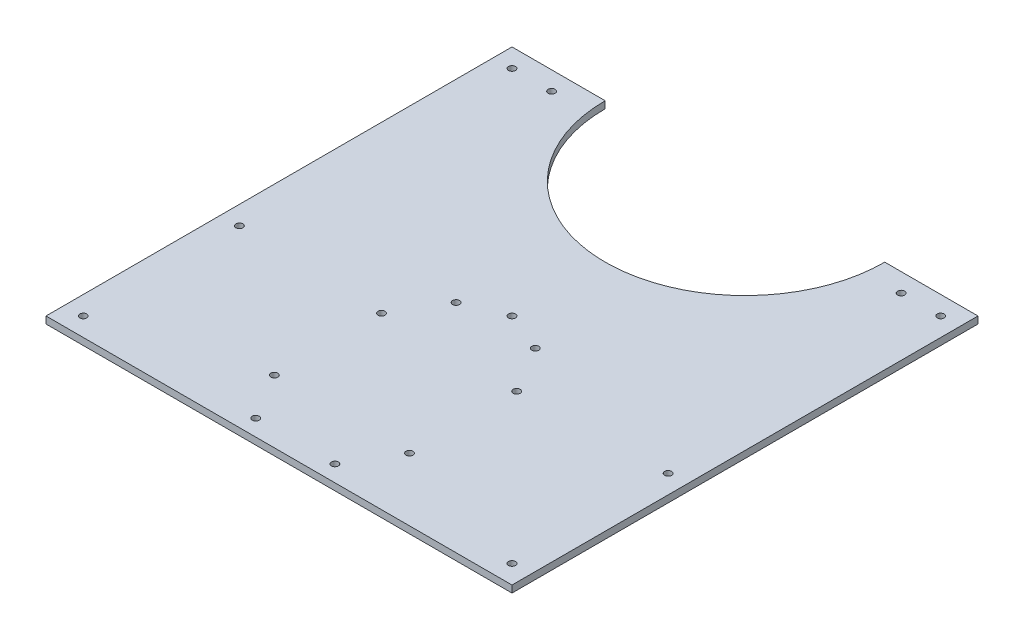
SolidWorks part; units mm, degrees
ref_plane "Front Plane" through (0, 0, 0) normal (0, 0, 1) x (1, 0, 0)
ref_plane "Top Plane" through (0, 0, 0) normal (0, 1, 0) x (1, 0, 0)
ref_plane "Right Plane" through (0, 0, 0) normal (1, 0, 0) x (0, 0, -1)
sketch "Sketch1" plane through (0, 0, 0) normal (0, 1, 0) x (1, 0, 0)
  line L0 (0, 100) -> (0, -100)
  line L1 (-100, -100) -> (100, -100)
  line L2 (-100, -100) -> (-100, 100)
  line L3 (-100, 100) -> (100, 100)
  line L4 (100, -100) -> (100, 100)
  line L5 (-100, -100) -> (100, 100) construction
  line L6 (-100, 100) -> (100, -100) construction
  line L7 (0, 0) -> (100, 0)
  line L8 (70, 25) -> (37.5, 25)
  line L9 (100, 60) -> (70, 60)
  line L10 (100, 60) -> (100, -10)
  line L11 (100, -10) -> (70, -10)
  line L12 (70, 60) -> (70, -10)
  line L13 (100, -65) -> (65, -65)
  line L14 (5, 11.85) -> (70, 11.85)
  line L15 (5, 11.85) -> (5, 38.15)
  line L16 (5, 38.15) -> (70, 38.15)
  line L17 (70, 11.85) -> (70, 38.15)
  line L18 (5, 11.85) -> (70, 38.15) construction
  line L19 (5, 38.15) -> (70, 11.85) construction
  line L20 (0, -50) -> (29, -50)
  line L21 (29, -93) -> (-29, -93)
  line L22 (29, -93) -> (29, -7)
  line L23 (29, -7) -> (-29, -7)
  line L24 (-29, -93) -> (-29, -7)
  line L25 (29, -93) -> (-29, -7) construction
  line L26 (29, -7) -> (-29, -93) construction
  line L27 (35, 38.15) -> (35, 11.85)
  line L28 (43, 38.15) -> (43, 11.85)
  line L29 (68, 11.85) -> (35, 11.85)
  line L30 (68, 11.85) -> (68, 38.15)
  line L31 (68, 38.15) -> (35, 38.15)
  line L32 (35, 11.85) -> (35, 38.15)
  line L33 (68, 11.85) -> (35, 38.15) construction
  line L34 (68, 38.15) -> (35, 11.85) construction
  line L35 (57, 38.15) -> (57, 11.85)
  line L36 (50, 38.15) -> (50, 11.85)
  line L37 (57, 38.15) -> (43, 38.15)
  line L38 (57, 38.15) -> (57, 11.85)
  line L39 (57, 11.85) -> (43, 11.85)
  line L40 (43, 38.15) -> (43, 11.85)
  circle A0 centre (0, 100) radius 60
  circle A1 centre (65, -65) radius 23.5
  circle A2 centre (65, -65) radius 28.5
  circle A3 centre (93.5, -65) radius 1.5
  circle A4 centre (17, -93) radius 1.5
  circle A5 centre (29, -73) radius 1.5
  circle A6 centre (57, 16.85) radius 1.5
  circle A7 centre (92, -92) radius 1.5
  circle A8 centre (92, -25) radius 1.5
  circle A9 centre (92, 92) radius 1.5
  circle A10 centre (75, 92) radius 1.5
  circle A11 centre (0, 0) radius 1.5
  point P0 (0, 0)
  point P27 (0, -50)
  point P40 (51.5, 25)
  dimension "D3" = 120
  dimension "D9" = 47
  dimension "D10" = 57
  dimension "D11" = 3
  dimension "D17" = 3
  dimension "D18" = 3
  dimension "D25" = 3
  dimension "D27" = 3
  dimension "D29" = 3
  dimension "D32" = 3
  dimension "D33" = 3
  dimension "D37" = 3
  dimension "D1" = 200
  dimension "D2" = 200
  dimension "D4" = 70
  dimension "D5" = 30
  dimension "D6" = 95
  dimension "D7" = 26.3
  dimension "D8" = 10
  dimension "D12" = 35
  dimension "D13" = 35
  dimension "D14" = 86
  dimension "D15" = 58
  dimension "D16" = 50
  dimension "D19" = 20
  dimension "D20" = 12
  dimension "D21" = 65
  dimension "D22" = 33
  dimension "D23" = 8
  dimension "D24" = 22
  dimension "D26" = 5
  dimension "D28" = 8
  dimension "D30" = 8
  dimension "D31" = 25
  dimension "D34" = 8
  dimension "D35" = 8
  dimension "D36" = 25
sketch "Sketch2" plane through (0, 0, 0) normal (0, 1, 0) x (1, 0, 0)
  line L0 (70, 25) -> (37.5, 25) construction
  line L1 (0, 0) -> (100, 0) construction
  line L2 (0, 100) -> (0, -100) construction
  line L3 (100, -65) -> (65, -65) construction
  line L4 (100, 60) -> (70, 60)
  line L5 (70, 60) -> (70, -10)
  line L6 (70, -10) -> (100, -10)
  line L7 (100, -10) -> (100, 60)
  line L8 (100, 60) -> (70, 60)
  line L9 (70, 60) -> (70, -10)
  line L10 (70, -10) -> (100, -10)
  line L11 (100, -10) -> (100, 60)
  line L12 (-100, -100) -> (100, -100)
  line L13 (100, -100) -> (100, 100)
  line L14 (100, 100) -> (-100, 100)
  line L15 (-100, 100) -> (-100, -100)
  line L16 (-100, -100) -> (100, -100)
  line L17 (100, -100) -> (100, 100)
  line L18 (100, 100) -> (60, 100)
  line L19 (-100, 100) -> (-100, -100)
  line L20 (-29, -93) -> (29, -93)
  line L21 (-29, -7) -> (-29, -93)
  line L22 (29, -7) -> (-29, -7)
  line L23 (29, -93) -> (29, -7)
  line L24 (-29, -93) -> (29, -93)
  line L25 (-29, -7) -> (-29, -93)
  line L26 (29, -7) -> (-29, -7)
  line L27 (29, -93) -> (29, -7)
  line L28 (5, 11.85) -> (70, 11.85)
  line L29 (70, 11.85) -> (70, 38.15)
  line L30 (70, 38.15) -> (5, 38.15)
  line L31 (5, 38.15) -> (5, 11.85)
  line L32 (5, 11.85) -> (70, 11.85)
  line L33 (70, 11.85) -> (70, 38.15)
  line L34 (70, 38.15) -> (5, 38.15)
  line L35 (5, 38.15) -> (5, 11.85)
  line L36 (57, 38.15) -> (57, 11.85) construction
  line L37 (57, 38.15) -> (57, 11.85) construction
  line L38 (57, 11.85) -> (43, 11.85) construction
  line L39 (57, 38.15) -> (43, 38.15) construction
  line L40 (43, 38.15) -> (43, 11.85) construction
  line L41 (43, 38.15) -> (43, 11.85) construction
  line L42 (35, 38.15) -> (35, 11.85) construction
  line L43 (68, 11.85) -> (35, 11.85) construction
  line L44 (68, 11.85) -> (68, 38.15) construction
  line L45 (68, 38.15) -> (35, 38.15) construction
  line L46 (35, 11.85) -> (35, 38.15) construction
  line L47 (0, -50) -> (29, -50) construction
  line L48 (50, 38.15) -> (50, 11.85) construction
  line L49 (70, 25) -> (37.5, 25)
  line L50 (0, 0) -> (100, 0)
  line L51 (0, 40) -> (0, -100)
  line L52 (100, -65) -> (65, -65)
  line L53 (57, 38.15) -> (57, 11.85)
  line L54 (57, 38.15) -> (57, 11.85)
  line L55 (57, 11.85) -> (43, 11.85)
  line L56 (57, 38.15) -> (43, 38.15)
  line L57 (43, 38.15) -> (43, 11.85)
  line L58 (43, 38.15) -> (43, 11.85)
  line L59 (35, 38.15) -> (35, 11.85)
  line L60 (68, 11.85) -> (35, 11.85)
  line L61 (68, 11.85) -> (68, 38.15)
  line L62 (68, 38.15) -> (35, 38.15)
  line L63 (35, 11.85) -> (35, 38.15)
  line L64 (0, -50) -> (29, -50)
  line L65 (50, 38.15) -> (50, 11.85)
  line L66 (-60, 100) -> (-100, 100)
  circle A1 centre (0, 100) radius 60
  arc A2 (-60, 100) -> (60, 100) centre (0, 100) ccw
  circle A3 centre (93.5, -65) radius 1.5
  circle A4 centre (93.5, -65) radius 1.5
  circle A5 centre (65, -65) radius 28.5
  circle A6 centre (65, -65) radius 28.5
  circle A7 centre (65, -65) radius 23.5
  circle A8 centre (65, -65) radius 23.5
  circle A9 centre (29, -73) radius 1.5
  circle A10 centre (29, -73) radius 1.5
  circle A11 centre (17, -93) radius 1.5
  circle A12 centre (17, -93) radius 1.5
  circle A13 centre (0, 0) radius 1.5
  circle A14 centre (0, 0) radius 1.5
  circle A15 centre (75, 92) radius 1.5
  circle A16 centre (75, 92) radius 1.5
  circle A17 centre (92, 92) radius 1.5
  circle A18 centre (92, 92) radius 1.5
  circle A19 centre (92, -25) radius 1.5
  circle A20 centre (92, -25) radius 1.5
  circle A21 centre (92, -92) radius 1.5
  circle A22 centre (92, -92) radius 1.5
  circle A23 centre (57, 16.85) radius 1.5
  circle A24 centre (57, 16.85) radius 1.5
  dimension "D1" = 0
  dimension "D2" = 0
  dimension "D3" = 0
  dimension "D4" = 0
  dimension "D5" = 0
  dimension "D6" = 0
  dimension "D7" = 0
  dimension "D8" = 0
  dimension "D9" = 0
  dimension "D10" = 0
  dimension "D11" = 0
  dimension "D12" = 0
  dimension "D13" = 0
  dimension "D14" = 0
  dimension "D15" = 0
  dimension "D16" = 0
sketch "Sketch3" plane through (0, 0, 0) normal (0, 1, 0) x (1, 0, 0)
  line L1 (-100, 100) -> (100, 100)
  line L2 (-100, 100) -> (-100, -100)
  line L3 (-100, -100) -> (100, -100)
  line L4 (100, 100) -> (100, -100)
extrude "Boss-Extrude1" add sketch "Sketch3" along normal blind 3
sketch "Sketch4" plane through (0, 3, 0) normal (0, 1, 0) x (1, 0, 0)
  line L0 (-100, -100) -> (100, 100) construction
  line L8 (-100, 100) -> (100, 100) construction
  circle A0 centre (92, 92) radius 1.5
  circle A1 centre (92, -92) radius 1.5
  circle A2 centre (-92, -92) radius 1.5
  circle A3 centre (-92, 92) radius 1.5
  circle A4 centre (92, -25) radius 1.5
  circle A6 centre (17, -93) radius 1.5
  circle A7 centre (29, -73) radius 1.5
  circle A8 centre (75, 92) radius 1.5
  circle A9 centre (29, -27) radius 1.5
  circle A10 centre (17, -7) radius 1.5
  circle A11 centre (-92, -25) radius 1.5
  circle A12 centre (-17, -93) radius 1.5
  circle A13 centre (-29, -73) radius 1.5
  circle A14 centre (-29, -27) radius 1.5
  circle A15 centre (-17, -7) radius 1.5
  circle A24 centre (0, 100) radius 60
  circle A25 centre (-75, 92) radius 1.5
  circle A26 centre (0, 0) radius 1.5
  point P12 (0, 0)
  dimension "D1" = 4
extrude "Cut-Extrude1" cut sketch "Sketch4" against normal blind 5
ref_plane "Plane1" through (0, 0, 0) normal (-1, 0, 0) x (0, 0, 1)
